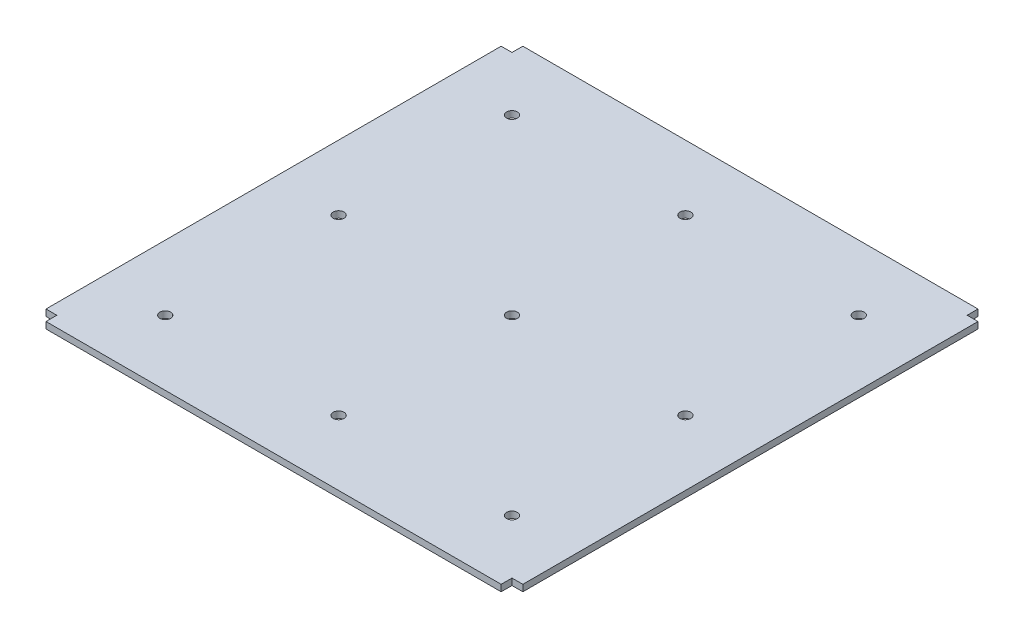
SolidWorks part; units mm, degrees
material "ABS"
ref_plane "Front Plane" through (0, 0, 0) normal (0, 0, 1) x (1, 0, 0)
ref_plane "Top Plane" through (0, 0, 0) normal (0, 1, 0) x (1, 0, 0)
ref_plane "Right Plane" through (0, 0, 0) normal (1, 0, 0) x (0, 0, -1)
sketch "Sketch1" plane through (0, 0, 0) normal (0, 1, 0) x (1, 0, 0)
  line L1 (0, -5) -> (210, -5)
  line L2 (-5, 0) -> (-5, 210)
  line L3 (0, 215) -> (210, 215)
  line L4 (215, 0) -> (215, 210)
  line L9 (-5, 210) -> (0, 210)
  line L10 (0, 215) -> (0, 210)
  line L13 (215, 210) -> (210, 210)
  line L14 (210, 215) -> (210, 210)
  line L17 (215, 0) -> (210, 0)
  line L18 (210, -5) -> (210, 0)
  line L21 (-5, 0) -> (0, 0)
  line L22 (0, -5) -> (0, 0)
  point P0 (0, 0)
  dimension "D1" = 220
  dimension "D2" = 5
extrude "Boss-Extrude1" add sketch "Sketch1" along normal blind 3
sketch "Sketch2" plane through (0, 3, 0) normal (0, 1, 0) x (1, 0, 0)
  line L0 (0, 0) -> (0, -5) construction
  line L1 (-5, 0) -> (0, 0) construction
  circle A0 centre (25, 25) radius 2.5
  dimension "D1" = 5
  dimension "D2" = 25
  dimension "D3" = 25
extrude "Cut-Extrude1" cut sketch "Sketch2" against normal through all
pattern_linear "LPattern1" count 3 spacing 80 along (1, 0, 0) count 3 spacing 80 along (0, 0, -1) of "Cut-Extrude1"
